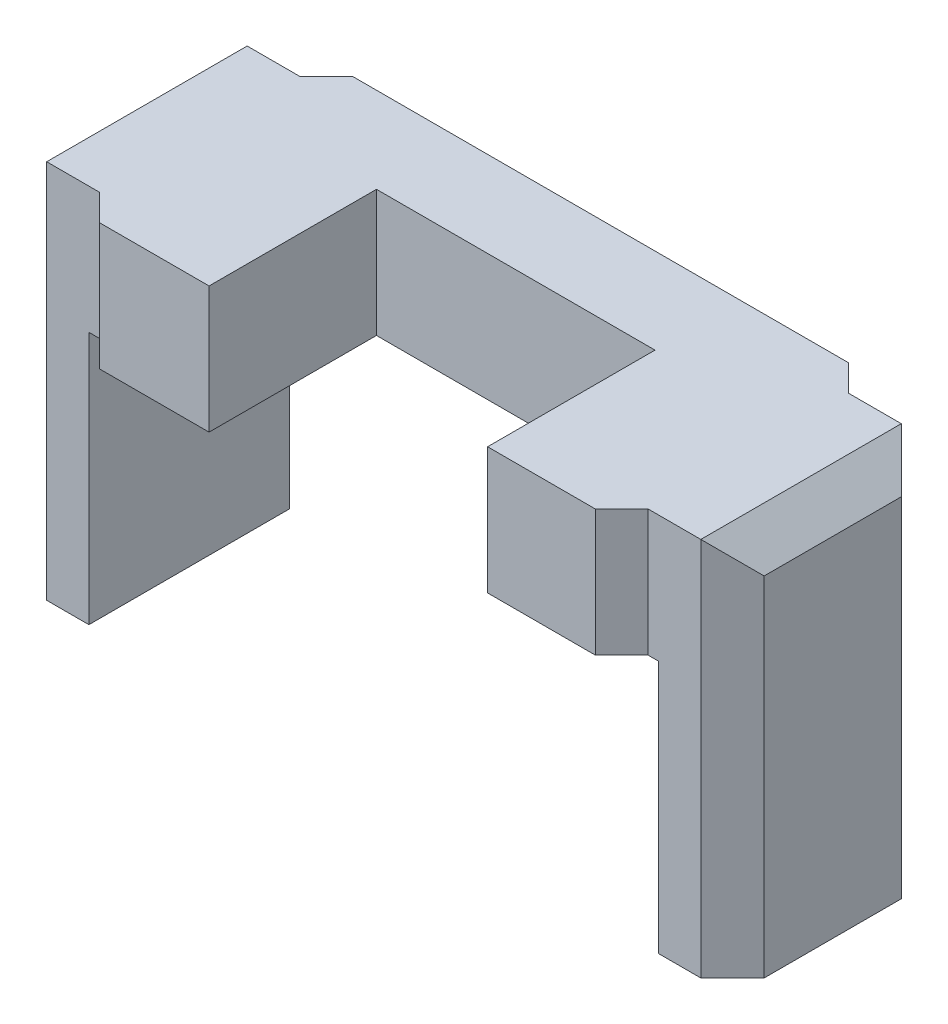
SolidWorks part; units mm, degrees
ref_plane "Front Plane" through (0, 0, 0) normal (0, 0, 1) x (1, 0, 0)
ref_plane "Top Plane" through (0, 0, 0) normal (0, 1, 0) x (1, 0, 0)
ref_plane "Right Plane" through (0, 0, 0) normal (1, 0, 0) x (0, 0, -1)
sketch "Sketch1" plane through (0, 0, 0) normal (0, 1, 0) x (1, 0, 0)
  line L0 (-12.75, 0) -> (12.75, 0) construction
  line L1 (-26, 12) -> (26, 12)
  line L2 (-26, 12) -> (-26, -12)
  line L3 (-26, -12) -> (26, -12)
  line L4 (26, 12) -> (26, -12)
  line L5 (-26, 12) -> (26, -12) construction
  line L6 (-26, -12) -> (26, 12) construction
  circle A0 centre (12.75, 0) radius 8.25
  circle A1 centre (-12.75, 0) radius 8.25
  point P0 (0, 0)
  point P9 (0, 0)
  dimension "D3" = 16.5
  dimension "D1" = 52
  dimension "D2" = 24
  dimension "D4" = 25.5
extrude "Boss-Extrude1" add sketch "Sketch1" along normal blind 12
sketch "Sketch2" plane through (0, 12, 0) normal (0, 1, 0) x (1, 0, 0)
  line L1 (-21.35, 8.85) -> (21.35, 8.85) construction
  line L2 (-21.35, 8.85) -> (-21.35, -8.85) construction
  line L3 (-21.35, -8.85) -> (21.35, -8.85) construction
  line L4 (21.35, 8.85) -> (21.35, -8.85) construction
  line L5 (-21.35, 8.85) -> (21.35, -8.85) construction
  line L6 (-21.35, -8.85) -> (21.35, 8.85) construction
  circle A0 centre (-21.35, 8.85) radius 1
  circle A1 centre (21.35, 8.85) radius 1
  circle A2 centre (21.35, -8.85) radius 1
  circle A3 centre (-21.35, -8.85) radius 1
  point P0 (0, 0)
  dimension "D3" = 2
  dimension "D1" = 17.7
  dimension "D2" = 42.7
extrude "Cut-Extrude1" cut sketch "Sketch2" against normal through all
sketch "Sketch3" plane through (0, 12, 0) normal (0, 1, 0) x (1, 0, 0)
  circle A20 centre (-21.35, 8.85) radius 1.75
  circle A21 centre (21.35, 8.85) radius 1.75
  circle A23 centre (21.35, -8.85) radius 1.75
  circle A24 centre (-21.35, -8.85) radius 1.75
  dimension "D1" = 3.5
extrude "Cut-Extrude2" cut sketch "Sketch3" against normal blind 1
sketch "Sketch4" plane through (0, 0, 0) normal (0, -1, 0) x (1, 0, 0)
  line L0 (26, -12) -> (-26, -12) construction
  line L1 (-6, -12) -> (6, -12)
  line L2 (-6, -12) -> (-6, -5)
  line L3 (-6, -5) -> (6, -5)
  line L4 (6, -12) -> (6, -5)
  line L5 (0, -5) -> (0, 0)
  line M14 (-26, -12) -> (26, -12)
  dimension "D1" = 7
  dimension "D2" = 12
extrude "Cut-Extrude3" cut sketch "Sketch4" against normal blind 5 contours L4 L3 L2 M14
fillet "Fillet3" radius 0.5 5 edges at (-6, 5, -8.5) (6, 5, -8.5) (6, 2.5, -5) (0, 5, -5) (-6, 2.5, -5)
chamfer "Chamfer1" distance 2.5 4 edges at (26, 6, 12) (26, 6, -12) (-26, 6, -12) (-26, 6, 12)
sketch "Sketch5" plane through (-26, 0, 0) normal (-1, 0, 0) x (0, 0, 1)
  line L4 (9.5, 12) -> (-9.5, 12)
  line L5 (-9.5, 12) -> (-9.5, 0)
  line L6 (-9.5, 0) -> (9.5, 0)
  line L7 (9.5, 0) -> (9.5, 12)
  line L8 (9.5, 12) -> (-9.5, 12)
  line L9 (-9.5, 12) -> (-9.5, 0)
  line L10 (-9.5, 0) -> (9.5, 0)
  line L11 (9.5, 0) -> (9.5, 12)
  dimension "D1" = 0
extrude "Boss-Extrude2" add sketch "Sketch5" along normal blind 8
sketch "Sketch6" plane through (0, 0, 0) normal (0, -1, 0) x (1, 0, 0)
  line L0 (-34, 9.5) -> (-34, -9.5)
  line L1 (-34, 9.5) -> (-26, 9.5) construction
  line L2 (-34, -9.5) -> (-34, 9.5) construction
  line L3 (-34, -9.5) -> (-27, -9.5)
  line L4 (-34, -9.5) -> (-26, -9.5) construction
  line L5 (-27, -9.5) -> (-27, 9.5)
  line L6 (-27, 9.5) -> (-34, 9.5)
  dimension "D1" = 7
extrude "Boss-Extrude3" add sketch "Sketch6" along normal blind 24 contours L6 L0 L3 L5
chamfer "Chamfer2" distance 3 angle 45 3 edges at (-34, -6, -9.5) (-34, -6, 9.5) (-34, 12, 0)
mirror "Mirror1" about plane through (0, 0, 0) normal (1, 0, 0) of "Boss-Extrude3", "Boss-Extrude2", "Chamfer2"
sketch "Sketch7" plane through (0, 0, 0) normal (0, -1, 0) x (1, 0, 0)
  line L0 (-23.5, 12) -> (23.5, 12) construction
  line L1 (-7, 16) -> (7, 16)
  line L2 (-7, 16) -> (-7, 8)
  line L3 (-7, 8) -> (7, 8)
  line L4 (7, 16) -> (7, 8)
  line L5 (-7, 16) -> (7, 8) construction
  line L6 (-7, 8) -> (7, 16) construction
  point P0 (0, 12)
  dimension "D1" = 8
  dimension "D2" = 14
extrude "Cut-Extrude4" cut sketch "Sketch7" against normal up to surface (5 mm away) up to face at (0, 5, -8.75)
fillet "Fillet4" radius 0.5 5 edges at (-7, 5, 10) (-7, 2.5, 8) (7, 5, 10) (7, 2.5, 8) (0, 5, 8)
sketch "Sketch8" plane through (0, 0, 0) normal (0, -1, 0) x (1, 0, 0)
  line L0 (-7, 12) -> (7, 12)
  line L1 (-6, -12) -> (6, -12)
  line L20 (23.5, 12) -> (7, 12)
  line L21 (7, 12) -> (7, 8.5)
  line L22 (6.5, 8) -> (-6.5, 8)
  line L23 (-7, 8.5) -> (-7, 12)
  line L24 (-7, 12) -> (-23.5, 12)
  line L25 (-23.5, 12) -> (-26, 9.5)
  line L26 (-26, 9.5) -> (-27, 9.5)
  line L27 (-27, 9.5) -> (-27, -9.5)
  line L28 (-27, -9.5) -> (-26, -9.5)
  line L29 (-26, -9.5) -> (-23.5, -12)
  line L30 (-23.5, -12) -> (-6, -12)
  line L31 (-6, -12) -> (-6, -5.5)
  line L32 (-5.5, -5) -> (5.5, -5)
  line L33 (6, -5.5) -> (6, -12)
  line L34 (6, -12) -> (23.5, -12)
  line L35 (23.5, -12) -> (26, -9.5)
  line L36 (26, -9.5) -> (27, -9.5)
  line L37 (27, -9.5) -> (27, 9.5)
  line L38 (27, 9.5) -> (26, 9.5)
  line L39 (26, 9.5) -> (23.5, 12)
  line L40 (23.5, 12) -> (7, 12)
  line L44 (-7, 12) -> (-23.5, 12)
  line L45 (-23.5, 12) -> (-26, 9.5)
  line L46 (-26, 9.5) -> (-27, 9.5)
  line L47 (-27, 9.5) -> (-27, -9.5)
  line L48 (-27, -9.5) -> (-26, -9.5)
  line L49 (-26, -9.5) -> (-23.5, -12)
  line L50 (-23.5, -12) -> (-6, -12)
  line L54 (6, -12) -> (23.5, -12)
  line L55 (23.5, -12) -> (26, -9.5)
  line L56 (26, -9.5) -> (27, -9.5)
  line L57 (27, -9.5) -> (27, 9.5)
  line L58 (27, 9.5) -> (26, 9.5)
  line L59 (26, 9.5) -> (23.5, 12)
  arc A4 (6.5, 8) -> (7, 8.5) centre (6.5, 8.5) ccw
  arc A5 (-7, 8.5) -> (-6.5, 8) centre (-6.5, 8.5) ccw
  arc A6 (-5.5, -5) -> (-6, -5.5) centre (-5.5, -5.5) ccw
  arc A7 (6, -5.5) -> (5.5, -5) centre (5.5, -5.5) ccw
  dimension "D1" = 0
extrude "Boss-Extrude4" add sketch "Sketch8" against normal up to surface (12 mm away) up to face at (-21.35, 12, 10.6)
sketch "Sketch9" plane through (0, 0, 0) normal (0, -1, 0) x (1, 0, 0)
  line L4 (-13.1098, -3.8664) -> (13.2892, -3.8664)
  line L5 (13.2892, -3.8664) -> (13.2892, 12.1336)
  line L6 (13.2892, 12.1336) -> (-13.1098, 12.1336)
  line L7 (-13.1098, 12.1336) -> (-13.1098, -3.8664)
  line L8 (-13.1098, -3.8664) -> (13.2892, -3.8664)
  line L9 (13.2892, -3.8664) -> (13.2892, 12.1336)
  line L10 (13.2892, 12.1336) -> (-13.1098, 12.1336)
  line L11 (-13.1098, 12.1336) -> (-13.1098, -3.8664)
  dimension "D1" = 0
extrude "Cut-Extrude5" cut sketch "Sketch9" against normal blind 13 contours L8 L11 L10 L9
